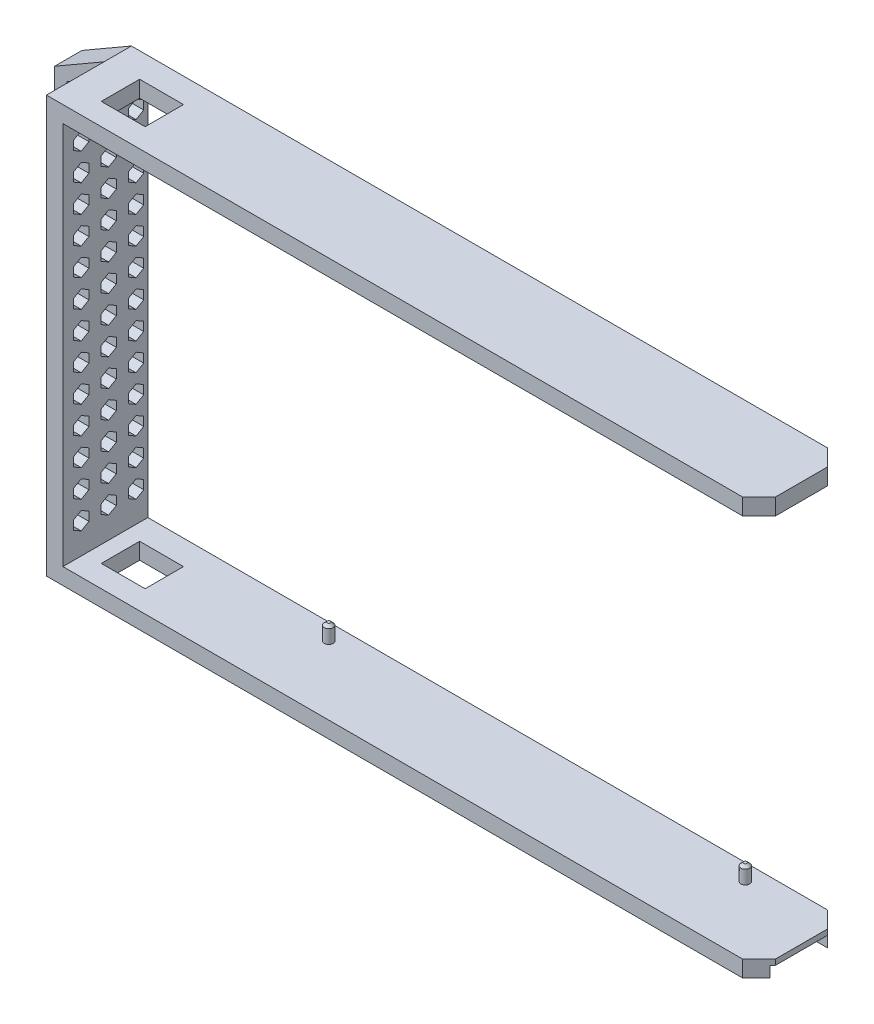
SolidWorks part; units mm, degrees
ref_plane "Alzado" through (0, 0, 0) normal (0, 0, 1) x (1, 0, 0)
ref_plane "Planta" through (0, 0, 0) normal (0, 1, 0) x (1, 0, 0)
ref_plane "Vista lateral" through (0, 0, 0) normal (1, 0, 0) x (0, 0, -1)
sketch "Sketch1" plane through (0, 0, 0) normal (0, 0, 1) x (1, 0, 0)
  line L5 (130, 76) -> (0, 76)
  line L6 (130, 76) -> (130, 73)
  line L7 (130, 73) -> (0, 73)
  line L8 (0, 76) -> (0, 73)
  line L9 (130, 0) -> (0, 0)
  line L10 (130, 0) -> (130, 3)
  line L11 (130, 3) -> (0, 3)
  line L12 (0, 0) -> (0, 3)
  line L13 (0, 76) -> (3, 76)
  line L14 (0, 76) -> (0, 0)
  line L15 (0, 0) -> (3, 0)
  line L16 (3, 76) -> (3, 0)
  point P12 (3.7282, 0)
extrude "Boss-Extrude1" add sketch "Sketch1" along normal blind 15.5 contours L16 L7 L14 L11
sketch "Sketch2" plane through (0, 0, 0) normal (0, -1, 0) x (1, 0, 0)
  line L2 (130, 3) -> (108, 3)
  line L3 (130, 3) -> (130, 13)
  line L4 (130, 13) -> (108, 13)
  line L5 (108, 3) -> (108, 13)
extrude "Cut-Extrude1" cut sketch "Sketch2" against normal blind 2 contours L3 L2 L5 L4
chamfer "Chamfer5" distance 2 angle 45 1 edges at (130, 1.5, 0)
sketch "Sketch3" plane through (0, 0, 0) normal (0, -1, 0) x (1, 0, 0)
  line L0 (130, 3) -> (130, 2) construction
  line L1 (128, 0) -> (130, 0)
  line L2 (128, 0) -> (128, 2.5)
  line L3 (128, 2.5) -> (130, 2.5)
  line L4 (130, 0) -> (130, 2.5)
extrude "Boss-Extrude2" add sketch "Sketch3" against normal blind 3
chamfer "Chamfer9" distance 3 angle 45 1 edges at (130, 1.5, 0)
chamfer "Chamfer10" distance 3 angle 45 1 edges at (130, 1.5, 15.5)
chamfer "Chamfer11" distance 3 angle 45 1 edges at (130, 74.5, 0)
chamfer "Chamfer12" distance 3 angle 45 1 edges at (130, 74.5, 15.5)
sketch "Sketch4" plane through (0, 76, 0) normal (0, 1, 0) x (1, 0, 0)
  line L0 (130, -6.7163) -> (14, -6.7163)
  line L1 (130, -12.5) -> (130, -3) construction
  line L2 (14, -15.5) -> (14, -11.5)
  line L3 (0, -15.5) -> (127, -15.5) construction
  line L5 (14, -11.5) -> (6, -11.5)
  line L6 (14, -11.5) -> (14, -4.5)
  line L7 (14, -4.5) -> (6, -4.5)
  line L8 (6, -11.5) -> (6, -4.5)
extrude "Cut-Extrude3" cut sketch "Sketch4" against normal blind 143 contours L8 L5 L6 L7
sketch "Sketch10" plane through (0, 76, 0) normal (0, 1, 0) x (1, 0, 0)
  line L0 (130, -7.75) -> (115, -7.75)
  line L1 (130, -12.5) -> (130, -3) construction
  line L2 (115, 0) -> (115, -3)
  line L3 (0, 0) -> (127, 0) construction
  circle A0 centre (115, -3) radius 0.8
extrude "Boss-Extrude5" add sketch "Sketch10" against normal blind 73 contours A0
sketch "Sketch14" plane through (0, 76, 0) normal (0, 1, 0) x (1, 0, 0)
  line L0 (130, -6.9193) -> (39, -6.9193)
  line L1 (130, -12.5) -> (130, -3) construction
  circle A0 centre (39, -3) radius 0.8
extrude "Boss-Extrude6" add sketch "Sketch14" against normal blind 73 contours A0
sketch "Sketch15" plane through (0, 0, 15.5) normal (0, 0, 1) x (1, 0, 0)
  line L0 (3, 38) -> (140.1413, 38)
  line L1 (3, 73) -> (3, 3) construction
  line L3 (115.9194, 38) -> (127.0648, 38)
  line L4 (115.9194, 38) -> (115.9194, 70)
  line L5 (115.9194, 70) -> (127.0648, 70)
  line L6 (127.0648, 38) -> (127.0648, 70)
  line L7 (109.1178, 38) -> (132.0541, 38)
  line L8 (109.1178, 38) -> (109.1178, 6)
  line L9 (109.1178, 6) -> (132.0541, 6)
  line L10 (132.0541, 38) -> (132.0541, 6)
  line L11 (32.7878, 38) -> (50.9796, 38)
  line L12 (32.7878, 38) -> (32.7878, 70)
  line L13 (32.7878, 70) -> (50.9796, 70)
  line L14 (50.9796, 38) -> (50.9796, 70)
  line L15 (37.5113, 38) -> (47.0501, 38)
  line L16 (37.5113, 38) -> (37.5113, 6)
  line L17 (37.5113, 6) -> (47.0501, 6)
  line L18 (47.0501, 38) -> (47.0501, 6)
  line L19 (115.9194, 70) -> (76.7632, 70)
  line L20 (115.9194, 70) -> (115.9194, 38)
  line L21 (115.9194, 38) -> (76.7632, 38)
  line L22 (76.7632, 70) -> (76.7632, 38)
extrude "Cut-Extrude7" cut sketch "Sketch15" against normal blind 73 contours L19 L22 L0 L4 | L0 L6 L5 L4 | L10 L0 L8 L9 | L18 L11 L16 L17 | L0 L11 L14 L13 L12
chamfer "Chamfer15" distance 0.5 angle 45 1 edges at (39, 6, 2.2)
chamfer "Chamfer16" distance 0.5 angle 45 3 edges at (39, 70, 2.2) (115, 70, 3.8) (115, 6, 2.2)
sketch "Sketch16" plane through (0, 0, 0) normal (-1, 0, 0) x (0, 0, 1)
  line L0 (7.1582, 66.9588) -> (8.561, 67.7686)
  line L1 (12.1582, 66.9588) -> (13.561, 67.7686)
  line L2 (13.561, 67.7686) -> (13.561, 69.3884)
  line L3 (13.561, 69.3884) -> (12.1582, 70.1982)
  line L4 (12.1582, 70.1982) -> (10.7555, 69.3884)
  line L5 (10.7555, 69.3884) -> (10.7555, 67.7686)
  line L6 (10.7555, 67.7686) -> (12.1582, 66.9588)
  line L7 (8.561, 67.7686) -> (8.561, 69.3884)
  line L8 (8.561, 69.3884) -> (7.1582, 70.1982)
  line L9 (7.1582, 70.1982) -> (5.7555, 69.3884)
  line L10 (5.7555, 69.3884) -> (5.7555, 67.7686)
  line L11 (5.7555, 67.7686) -> (7.1582, 66.9588)
  line L12 (2.1582, 66.9588) -> (3.561, 67.7686)
  line L13 (3.561, 67.7686) -> (3.561, 69.3884)
  line L14 (3.561, 69.3884) -> (2.1582, 70.1982)
  line L15 (2.1582, 70.1982) -> (0.7555, 69.3884)
  line L16 (0.7555, 69.3884) -> (0.7555, 67.7686)
  line L17 (0.7555, 67.7686) -> (2.1582, 66.9588)
  line L18 (7.1582, 61.9588) -> (8.561, 62.7686)
  line L19 (8.561, 62.7686) -> (8.561, 64.3884)
  line L20 (8.561, 64.3884) -> (7.1582, 65.1982)
  line L21 (7.1582, 65.1982) -> (5.7555, 64.3884)
  line L22 (5.7555, 64.3884) -> (5.7555, 62.7686)
  line L23 (5.7555, 62.7686) -> (7.1582, 61.9588)
  line L24 (2.1582, 61.9588) -> (3.561, 62.7686)
  line L25 (3.561, 62.7686) -> (3.561, 64.3884)
  line L26 (3.561, 64.3884) -> (2.1582, 65.1982)
  line L27 (2.1582, 65.1982) -> (0.7555, 64.3884)
  line L28 (0.7555, 64.3884) -> (0.7555, 62.7686)
  line L29 (0.7555, 62.7686) -> (2.1582, 61.9588)
  line L30 (7.1582, 56.9588) -> (8.561, 57.7687)
  line L31 (8.561, 57.7687) -> (8.561, 59.3884)
  line L32 (8.561, 59.3884) -> (7.1582, 60.1982)
  line L33 (7.1582, 60.1982) -> (5.7555, 59.3884)
  line L34 (5.7555, 59.3884) -> (5.7555, 57.7687)
  line L35 (5.7555, 57.7687) -> (7.1582, 56.9588)
  line L36 (2.1582, 56.9588) -> (3.561, 57.7687)
  line L37 (3.561, 57.7687) -> (3.561, 59.3884)
  line L38 (3.561, 59.3884) -> (2.1582, 60.1982)
  line L39 (2.1582, 60.1982) -> (0.7555, 59.3884)
  line L40 (0.7555, 59.3884) -> (0.7555, 57.7687)
  line L41 (0.7555, 57.7687) -> (2.1582, 56.9588)
  line L42 (7.1582, 51.9588) -> (8.561, 52.7687)
  line L43 (8.561, 52.7687) -> (8.561, 54.3884)
  line L44 (8.561, 54.3884) -> (7.1582, 55.1983)
  line L45 (7.1582, 55.1983) -> (5.7555, 54.3884)
  line L46 (5.7555, 54.3884) -> (5.7555, 52.7687)
  line L47 (5.7555, 52.7687) -> (7.1582, 51.9588)
  line L48 (2.1582, 51.9588) -> (3.561, 52.7687)
  line L49 (3.561, 52.7687) -> (3.561, 54.3884)
  line L50 (3.561, 54.3884) -> (2.1582, 55.1983)
  line L51 (2.1582, 55.1983) -> (0.7555, 54.3884)
  line L52 (0.7555, 54.3884) -> (0.7555, 52.7687)
  line L53 (0.7555, 52.7687) -> (2.1582, 51.9588)
  line L54 (7.1582, 46.9588) -> (8.561, 47.7687)
  line L55 (8.561, 47.7687) -> (8.561, 49.3884)
  line L56 (8.561, 49.3884) -> (7.1582, 50.1983)
  line L57 (7.1582, 50.1983) -> (5.7555, 49.3884)
  line L58 (5.7555, 49.3884) -> (5.7555, 47.7687)
  line L59 (5.7555, 47.7687) -> (7.1582, 46.9588)
  line L60 (2.1582, 46.9588) -> (3.561, 47.7687)
  line L61 (3.561, 47.7687) -> (3.561, 49.3884)
  line L62 (3.561, 49.3884) -> (2.1582, 50.1983)
  line L63 (2.1582, 50.1983) -> (0.7555, 49.3884)
  line L64 (0.7555, 49.3884) -> (0.7555, 47.7687)
  line L65 (0.7555, 47.7687) -> (2.1582, 46.9588)
  line L66 (7.1582, 41.9588) -> (8.561, 42.7687)
  line L67 (8.561, 42.7687) -> (8.561, 44.3884)
  line L68 (8.561, 44.3884) -> (7.1582, 45.1983)
  line L69 (7.1582, 45.1983) -> (5.7555, 44.3884)
  line L70 (5.7555, 44.3884) -> (5.7555, 42.7687)
  line L71 (5.7555, 42.7687) -> (7.1582, 41.9588)
  line L72 (2.1582, 41.9588) -> (3.561, 42.7687)
  line L73 (3.561, 42.7687) -> (3.561, 44.3884)
  line L74 (3.561, 44.3884) -> (2.1582, 45.1983)
  line L75 (2.1582, 45.1983) -> (0.7555, 44.3884)
  line L76 (0.7555, 44.3884) -> (0.7555, 42.7687)
  line L77 (0.7555, 42.7687) -> (2.1582, 41.9588)
  line L78 (7.1582, 36.9588) -> (8.561, 37.7687)
  line L79 (8.561, 37.7687) -> (8.561, 39.3884)
  line L80 (8.561, 39.3884) -> (7.1582, 40.1983)
  line L81 (7.1582, 40.1983) -> (5.7555, 39.3884)
  line L82 (5.7555, 39.3884) -> (5.7555, 37.7687)
  line L83 (5.7555, 37.7687) -> (7.1582, 36.9588)
  line L84 (2.1582, 36.9588) -> (3.561, 37.7687)
  line L85 (3.561, 37.7687) -> (3.561, 39.3884)
  line L86 (3.561, 39.3884) -> (2.1582, 40.1983)
  line L87 (2.1582, 40.1983) -> (0.7555, 39.3884)
  line L88 (0.7555, 39.3884) -> (0.7555, 37.7687)
  line L89 (0.7555, 37.7687) -> (2.1582, 36.9588)
  line L90 (7.1582, 31.9588) -> (8.561, 32.7687)
  line L91 (8.561, 32.7687) -> (8.561, 34.3884)
  line L92 (8.561, 34.3884) -> (7.1582, 35.1983)
  line L93 (7.1582, 35.1983) -> (5.7555, 34.3884)
  line L94 (5.7555, 34.3884) -> (5.7555, 32.7687)
  line L95 (5.7555, 32.7687) -> (7.1582, 31.9588)
  line L96 (2.1582, 31.9588) -> (3.561, 32.7687)
  line L97 (3.561, 32.7687) -> (3.561, 34.3884)
  line L98 (3.561, 34.3884) -> (2.1582, 35.1983)
  line L99 (2.1582, 35.1983) -> (0.7555, 34.3884)
  line L100 (0.7555, 34.3884) -> (0.7555, 32.7687)
  line L101 (0.7555, 32.7687) -> (2.1582, 31.9588)
  line L102 (7.1582, 26.9588) -> (8.561, 27.7687)
  line L103 (8.561, 27.7687) -> (8.561, 29.3884)
  line L104 (8.561, 29.3884) -> (7.1582, 30.1983)
  line L105 (7.1582, 30.1983) -> (5.7555, 29.3884)
  line L106 (5.7555, 29.3884) -> (5.7555, 27.7687)
  line L107 (5.7555, 27.7687) -> (7.1582, 26.9588)
  line L108 (2.1582, 26.9588) -> (3.561, 27.7687)
  line L109 (3.561, 27.7687) -> (3.561, 29.3884)
  line L110 (3.561, 29.3884) -> (2.1582, 30.1983)
  line L111 (2.1582, 30.1983) -> (0.7555, 29.3884)
  line L112 (0.7555, 29.3884) -> (0.7555, 27.7687)
  line L113 (0.7555, 27.7687) -> (2.1582, 26.9588)
  line L114 (7.1582, 21.9589) -> (8.561, 22.7687)
  line L115 (8.561, 22.7687) -> (8.561, 24.3884)
  line L116 (8.561, 24.3884) -> (7.1582, 25.1983)
  line L117 (7.1582, 25.1983) -> (5.7555, 24.3884)
  line L118 (5.7555, 24.3884) -> (5.7555, 22.7687)
  line L119 (5.7555, 22.7687) -> (7.1582, 21.9589)
  line L120 (2.1582, 21.9589) -> (3.561, 22.7687)
  line L121 (3.561, 22.7687) -> (3.561, 24.3884)
  line L122 (3.561, 24.3884) -> (2.1582, 25.1983)
  line L123 (2.1582, 25.1983) -> (0.7555, 24.3884)
  line L124 (0.7555, 24.3884) -> (0.7555, 22.7687)
  line L125 (0.7555, 22.7687) -> (2.1582, 21.9589)
  line L126 (7.1582, 16.9589) -> (8.561, 17.7687)
  line L127 (8.561, 17.7687) -> (8.561, 19.3885)
  line L128 (8.561, 19.3885) -> (7.1582, 20.1983)
  line L129 (7.1582, 20.1983) -> (5.7555, 19.3885)
  line L130 (5.7555, 19.3885) -> (5.7555, 17.7687)
  line L131 (5.7555, 17.7687) -> (7.1582, 16.9589)
  line L132 (2.1582, 16.9589) -> (3.561, 17.7687)
  line L133 (3.561, 17.7687) -> (3.561, 19.3885)
  line L134 (3.561, 19.3885) -> (2.1582, 20.1983)
  line L135 (2.1582, 20.1983) -> (0.7555, 19.3885)
  line L136 (0.7555, 19.3885) -> (0.7555, 17.7687)
  line L137 (0.7555, 17.7687) -> (2.1582, 16.9589)
  line L138 (7.1582, 11.9589) -> (8.561, 12.7687)
  line L139 (8.561, 12.7687) -> (8.561, 14.3885)
  line L140 (8.561, 14.3885) -> (7.1582, 15.1983)
  line L141 (7.1582, 15.1983) -> (5.7555, 14.3885)
  line L142 (5.7555, 14.3885) -> (5.7555, 12.7687)
  line L143 (5.7555, 12.7687) -> (7.1582, 11.9589)
  line L144 (2.1582, 11.9589) -> (3.561, 12.7687)
  line L145 (3.561, 12.7687) -> (3.561, 14.3885)
  line L146 (3.561, 14.3885) -> (2.1582, 15.1983)
  line L147 (2.1582, 15.1983) -> (0.7555, 14.3885)
  line L148 (0.7555, 14.3885) -> (0.7555, 12.7687)
  line L149 (0.7555, 12.7687) -> (2.1582, 11.9589)
  line L150 (7.1582, 6.9589) -> (8.561, 7.7687)
  line L151 (8.561, 7.7687) -> (8.561, 9.3885)
  line L152 (8.561, 9.3885) -> (7.1582, 10.1983)
  line L153 (7.1582, 10.1983) -> (5.7555, 9.3885)
  line L154 (5.7555, 9.3885) -> (5.7555, 7.7687)
  line L155 (5.7555, 7.7687) -> (7.1582, 6.9589)
  line L156 (2.1582, 6.9589) -> (3.561, 7.7687)
  line L157 (3.561, 7.7687) -> (3.561, 9.3885)
  line L158 (3.561, 9.3885) -> (2.1582, 10.1983)
  line L159 (2.1582, 10.1983) -> (0.7555, 9.3885)
  line L160 (0.7555, 9.3885) -> (0.7555, 7.7687)
  line L161 (0.7555, 7.7687) -> (2.1582, 6.9589)
  line L162 (12.1582, 61.9588) -> (13.561, 62.7686)
  line L163 (13.561, 62.7686) -> (13.561, 64.3884)
  line L164 (13.561, 64.3884) -> (12.1582, 65.1982)
  line L165 (12.1582, 65.1982) -> (10.7555, 64.3884)
  line L166 (10.7555, 64.3884) -> (10.7555, 62.7686)
  line L167 (10.7555, 62.7686) -> (12.1582, 61.9588)
  line L168 (12.1582, 56.9588) -> (13.561, 57.7687)
  line L169 (13.561, 57.7687) -> (13.561, 59.3884)
  line L170 (13.561, 59.3884) -> (12.1582, 60.1982)
  line L171 (12.1582, 60.1982) -> (10.7555, 59.3884)
  line L172 (10.7555, 59.3884) -> (10.7555, 57.7687)
  line L173 (10.7555, 57.7687) -> (12.1582, 56.9588)
  line L174 (12.1582, 51.9588) -> (13.561, 52.7687)
  line L175 (13.561, 52.7687) -> (13.561, 54.3884)
  line L176 (13.561, 54.3884) -> (12.1582, 55.1983)
  line L177 (12.1582, 55.1983) -> (10.7555, 54.3884)
  line L178 (10.7555, 54.3884) -> (10.7555, 52.7687)
  line L179 (10.7555, 52.7687) -> (12.1582, 51.9588)
  line L180 (12.1582, 46.9588) -> (13.561, 47.7687)
  line L181 (13.561, 47.7687) -> (13.561, 49.3884)
  line L182 (13.561, 49.3884) -> (12.1582, 50.1983)
  line L183 (12.1582, 50.1983) -> (10.7555, 49.3884)
  line L184 (10.7555, 49.3884) -> (10.7555, 47.7687)
  line L185 (10.7555, 47.7687) -> (12.1582, 46.9588)
  line L186 (12.1582, 41.9588) -> (13.561, 42.7687)
  line L187 (13.561, 42.7687) -> (13.561, 44.3884)
  line L188 (13.561, 44.3884) -> (12.1582, 45.1983)
  line L189 (12.1582, 45.1983) -> (10.7555, 44.3884)
  line L190 (10.7555, 44.3884) -> (10.7555, 42.7687)
  line L191 (10.7555, 42.7687) -> (12.1582, 41.9588)
  line L192 (12.1582, 36.9588) -> (13.561, 37.7687)
  line L193 (13.561, 37.7687) -> (13.561, 39.3884)
  line L194 (13.561, 39.3884) -> (12.1582, 40.1983)
  line L195 (12.1582, 40.1983) -> (10.7555, 39.3884)
  line L196 (10.7555, 39.3884) -> (10.7555, 37.7687)
  line L197 (10.7555, 37.7687) -> (12.1582, 36.9588)
  line L198 (12.1582, 31.9588) -> (13.561, 32.7687)
  line L199 (13.561, 32.7687) -> (13.561, 34.3884)
  line L200 (13.561, 34.3884) -> (12.1582, 35.1983)
  line L201 (12.1582, 35.1983) -> (10.7555, 34.3884)
  line L202 (10.7555, 34.3884) -> (10.7555, 32.7687)
  line L203 (10.7555, 32.7687) -> (12.1582, 31.9588)
  line L204 (12.1582, 26.9588) -> (13.561, 27.7687)
  line L205 (13.561, 27.7687) -> (13.561, 29.3884)
  line L206 (13.561, 29.3884) -> (12.1582, 30.1983)
  line L207 (12.1582, 30.1983) -> (10.7555, 29.3884)
  line L208 (10.7555, 29.3884) -> (10.7555, 27.7687)
  line L209 (10.7555, 27.7687) -> (12.1582, 26.9588)
  line L210 (12.1582, 21.9589) -> (13.561, 22.7687)
  line L211 (13.561, 22.7687) -> (13.561, 24.3884)
  line L212 (13.561, 24.3884) -> (12.1582, 25.1983)
  line L213 (12.1582, 25.1983) -> (10.7555, 24.3884)
  line L214 (10.7555, 24.3884) -> (10.7555, 22.7687)
  line L215 (10.7555, 22.7687) -> (12.1582, 21.9589)
  line L216 (12.1582, 16.9589) -> (13.561, 17.7687)
  line L217 (13.561, 17.7687) -> (13.561, 19.3885)
  line L218 (13.561, 19.3885) -> (12.1582, 20.1983)
  line L219 (12.1582, 20.1983) -> (10.7555, 19.3885)
  line L220 (10.7555, 19.3885) -> (10.7555, 17.7687)
  line L221 (10.7555, 17.7687) -> (12.1582, 16.9589)
  line L222 (12.1582, 11.9589) -> (13.561, 12.7687)
  line L223 (13.561, 12.7687) -> (13.561, 14.3885)
  line L224 (13.561, 14.3885) -> (12.1582, 15.1983)
  line L225 (12.1582, 15.1983) -> (10.7555, 14.3885)
  line L226 (10.7555, 14.3885) -> (10.7555, 12.7687)
  line L227 (10.7555, 12.7687) -> (12.1582, 11.9589)
  line L228 (12.1582, 6.9589) -> (13.561, 7.7687)
  line L229 (13.561, 7.7687) -> (13.561, 9.3885)
  line L230 (13.561, 9.3885) -> (12.1582, 10.1983)
  line L231 (12.1582, 10.1983) -> (10.7555, 9.3885)
  line L232 (10.7555, 9.3885) -> (10.7555, 7.7687)
  line L233 (10.7555, 7.7687) -> (12.1582, 6.9589)
  circle A0 centre (12.1582, 68.5785) radius 1.4027 construction
  dimension "D1" = 3
  dimension "D2" = 13
extrude "Cut-Extrude8" cut sketch "Sketch16" against normal blind 73
sketch "Sketch17" plane through (0, 0, 0) normal (-1, 0, 0) x (0, 0, 1)
  line L0 (0, 76) -> (0, 0) construction
  line L1 (15.5, 76) -> (0, 76)
  line L2 (15.5, 76) -> (15.5, 71)
  line L3 (15.5, 71) -> (0, 71)
  line L4 (0, 76) -> (0, 71)
  line L7 (15.5, 0) -> (0, 0)
  line L8 (15.5, 0) -> (15.5, 5)
  line L9 (15.5, 5) -> (0, 5)
  line L10 (0, 0) -> (0, 5)
sketch "Sketch18" plane through (0, 0, 0) normal (0, 0, 1) x (1, 0, 0)
  line L0 (0, 76) -> (0, 73.3962)
  line L1 (0, 76) -> (0, 0) construction
  line L2 (0, 76) -> (0, 73.3962)
  line L6 (0, 76) -> (-9.0198, 70.7924)
  line L7 (-9.0198, 70.7924) -> (-9.0198, 60.3772)
  line L8 (-9.0198, 60.3772) -> (0, 55.1696)
  line L12 (0, 73.3962) -> (-6.7649, 69.4905)
  line L13 (-6.7649, 69.4905) -> (-6.7649, 61.6791)
  line L14 (-6.7649, 61.6791) -> (0, 57.7734)
  line L15 (0, 57.7734) -> (0, 55.1696)
  line L16 (6.7649, 65.5848) -> (6.7649, 69.4905)
  line L17 (9.0198, 65.5848) -> (9.0198, 70.7924)
  line L18 (4.5099, 73.3962) -> (0, 76)
  line L19 (3.3824, 71.4434) -> (0, 73.3962)
  line L20 (0, 57.7734) -> (0, 55.1696)
  line L21 (0, 57.7734) -> (3.3824, 59.7263)
  line L22 (0, 55.1696) -> (4.5099, 57.7734)
  line L25 (0, 18.2266) -> (0, 20.8304)
  line L26 (0, 18.2266) -> (0, 20.8304)
  line L27 (-6.7649, 14.3209) -> (0, 18.2266)
  line L28 (-6.7649, 6.5095) -> (-6.7649, 14.3209)
  line L29 (0, 2.6038) -> (-6.7649, 6.5095)
  line L30 (-9.0198, 15.6228) -> (0, 20.8304)
  line L31 (-9.0198, 5.2076) -> (-9.0198, 15.6228)
  line L32 (0, 0) -> (-9.0198, 5.2076)
  line L33 (0, 0) -> (0, 2.6038)
  line L34 (0, 0) -> (0, 2.6038)
extrude "Boss-Extrude9" add sketch "Sketch18" along normal blind 5 contours L15 L14 L13 L12 L0 L6 L7 L8 | L32 L33 L29 L28 L27 L25 L30 L31
